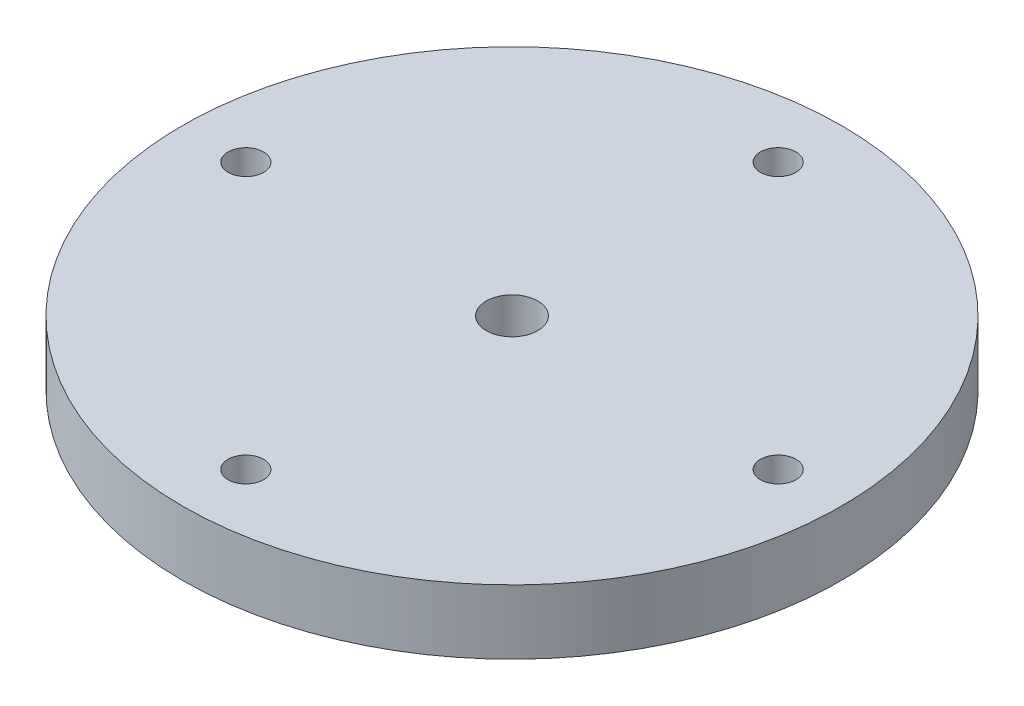
SolidWorks part; units mm, degrees
ref_plane "Front Plane" through (0, 0, 0) normal (0, 0, 1) x (1, 0, 0)
ref_plane "Top Plane" through (0, 0, 0) normal (0, 1, 0) x (1, 0, 0)
ref_plane "Right Plane" through (0, 0, 0) normal (1, 0, 0) x (0, 0, -1)
sketch "Sketch1" plane through (0, 0, 0) normal (0, 1, 0) x (1, 0, 0)
  circle A1 centre (0, 0) radius 32.5
  point P0 (0, 0)
  dimension "D1" = 65
extrude "Boss-Extrude1" add sketch "Sketch1" along normal blind 6.35
sketch "Esquisse1" plane through (0, 6.35, 0) normal (0, 1, 0) x (1, 0, 0)
  circle A0 centre (0, 0) radius 2.54
  dimension "D1" = 5.08
extrude "Enlèv. mat.-Extru.1" cut sketch "Esquisse1" against normal through all
sketch "Esquisse2" plane through (0, 6.35, 0) normal (0, 1, 0) x (1, 0, 0)
  circle A0 centre (0, 0) radius 26.25
  dimension "D1" = 52.5
sketch "Esquisse3" plane through (0, 6.35, 0) normal (0, 1, 0) x (1, 0, 0)
  circle A0 centre (0, -26.25) radius 1.75
  circle A1 centre (0, 0) radius 26.25 construction
  circle A2 centre (26.25, 0) radius 1.75
  circle A3 centre (0, 26.25) radius 1.75
  circle A4 centre (-26.25, 0) radius 1.75
  point P10 (0, 0)
  point P12 (0, 0)
  point P13 (0, 0)
  dimension "D1" = 3.5
extrude "Enlèv. mat.-Extru.2" cut sketch "Esquisse3" against normal through all
